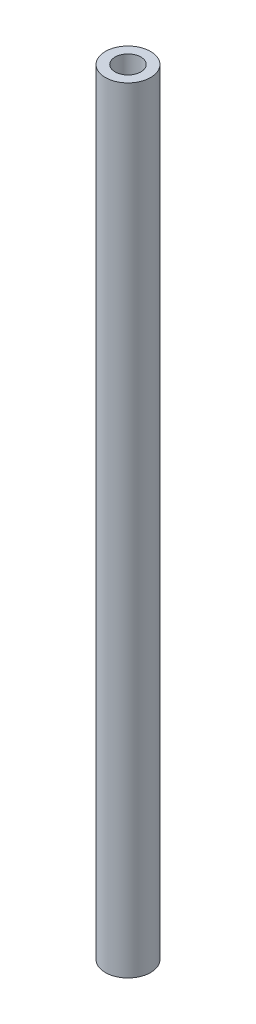
SolidWorks part; units mm, degrees
ref_plane "前视基准面" through (0, 0, 0) normal (0, 0, 1) x (1, 0, 0)
ref_plane "上视基准面" through (0, 0, 0) normal (0, 1, 0) x (1, 0, 0)
ref_plane "右视基准面" through (0, 0, 0) normal (1, 0, 0) x (0, 0, -1)
other "Configuration Table"
sketch "草图1" plane through (0, 0, 0) normal (0, 1, 0) x (1, 0, 0)
  circle A0 centre (0, 0) radius 1.75
  circle A1 centre (0, 0) radius 1
  dimension "D1" = 3.5
  dimension "D2" = 2
extrude "凸台-拉伸1" add sketch "草图1" along normal blind 60
